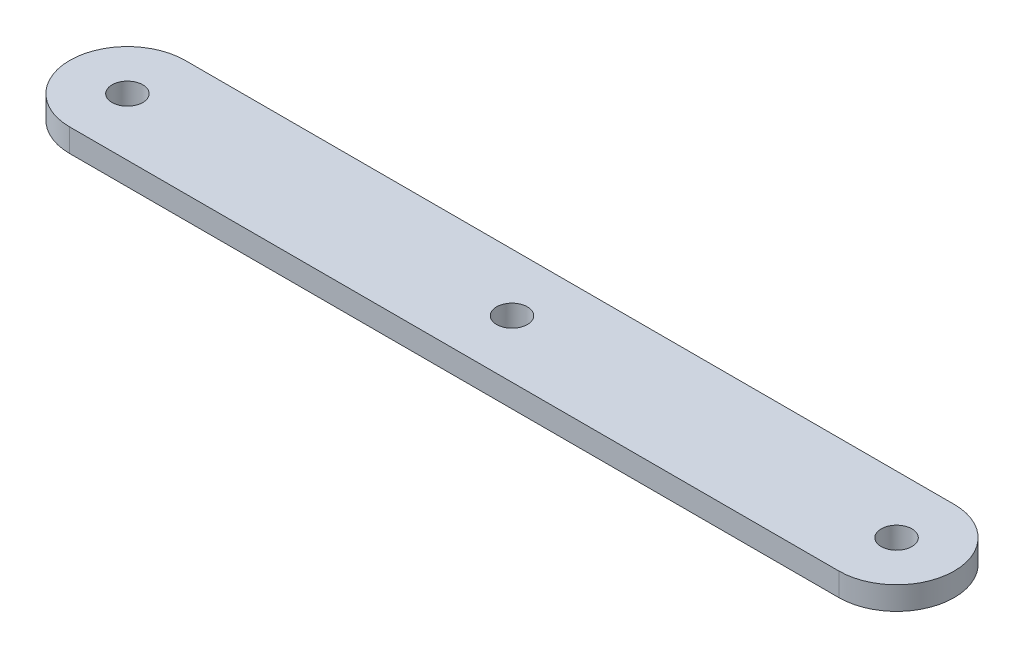
SolidWorks part; units mm, degrees
ref_plane "Front Plane" through (0, 0, 0) normal (0, 0, 1) x (1, 0, 0)
ref_plane "Top Plane" through (0, 0, 0) normal (0, 1, 0) x (1, 0, 0)
ref_plane "Right Plane" through (0, 0, 0) normal (1, 0, 0) x (0, 0, -1)
sketch "Sketch1" plane through (0, 0, 0) normal (0, 1, 0) x (1, 0, 0)
  line L1 (50, -7.5) -> (-50, -7.5)
  line L3 (50, 7.5) -> (-50, 7.5)
  line L5 (50, -7.5) -> (-50, 7.5) construction
  line L6 (50, 7.5) -> (-50, -7.5) construction
  arc A0 (-50, -7.5) -> (-50, 7.5) centre (-50, 0) cw
  arc A1 (50, 7.5) -> (50, -7.5) centre (50, 0) cw
  point P0 (0, 0)
  dimension "D1" = 100
  dimension "D2" = 15
extrude "Boss-Extrude1" add sketch "Sketch1" along normal blind 3
sketch "Sketch4" plane through (0, 3, 0) normal (0, 1, 0) x (1, 0, 0)
  circle A0 centre (-50, 0) radius 2
  circle A1 centre (50, 0) radius 2
  arc A2 (-50, 7.5) -> (-50, -7.5) centre (-50, 0) ccw construction
  arc A3 (50, -7.5) -> (50, 7.5) centre (50, 0) ccw construction
  point P6 (0, 0)
  point P10 (-57.5, 0)
  point P11 (0, 0)
  point P15 (57.5, 0)
  dimension "D1" = 4
extrude "Cut-Extrude1" cut sketch "Sketch4" against normal blind 10
sketch "Sketch5" plane through (0, 3, 0) normal (0, 1, 0) x (1, 0, 0)
  circle A0 centre (0, 0) radius 2
  arc A1 (-50, 7.5) -> (-50, -7.5) centre (-50, 0) ccw construction
  point P3 (0, 0)
  point P7 (-57.5, 0)
  dimension "D1" = 4
extrude "Cut-Extrude2" cut sketch "Sketch5" against normal blind 10
